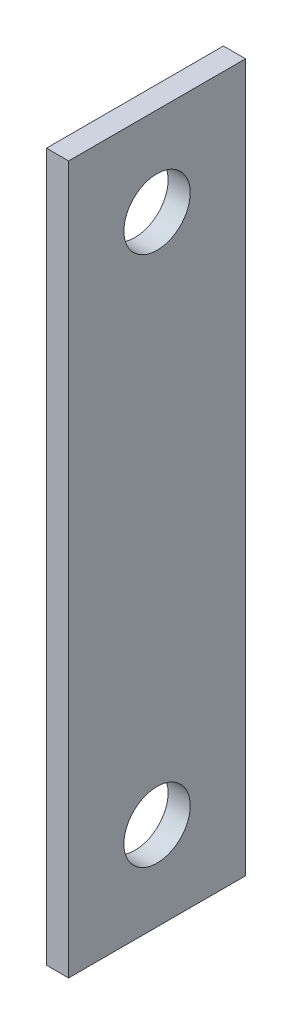
SolidWorks part; units mm, degrees
ref_plane "Front Plane" through (0, 0, 0) normal (0, 0, 1) x (1, 0, 0)
ref_plane "Top Plane" through (0, 0, 0) normal (0, 1, 0) x (1, 0, 0)
ref_plane "Right Plane" through (0, 0, 0) normal (1, 0, 0) x (0, 0, -1)
sketch "Sketch1" plane through (0, 0, 0) normal (1, 0, 0) x (0, 0, -1)
  line L1 (-12.7, -50.8) -> (12.7, -50.8)
  line L2 (-12.7, -50.8) -> (-12.7, 50.8)
  line L3 (-12.7, 50.8) -> (12.7, 50.8)
  line L4 (12.7, -50.8) -> (12.7, 50.8)
  line L5 (-12.7, -50.8) -> (12.7, 50.8) construction
  line L6 (-12.7, 50.8) -> (12.7, -50.8) construction
  circle A0 centre (0, 38.1) radius 4.7625
  circle A1 centre (0, -38.1) radius 4.7625
  point P0 (0, 0)
  dimension "D3" = 9.525
  dimension "D4" = 9.525
  dimension "D1" = 101.6
  dimension "D2" = 25.4
  dimension "D5" = 12.7
  dimension "D6" = 12.7
  dimension "D7" = 12.7
  dimension "D8" = 12.7
extrude "Boss-Extrude1" add sketch "Sketch1" along normal blind 3.175
